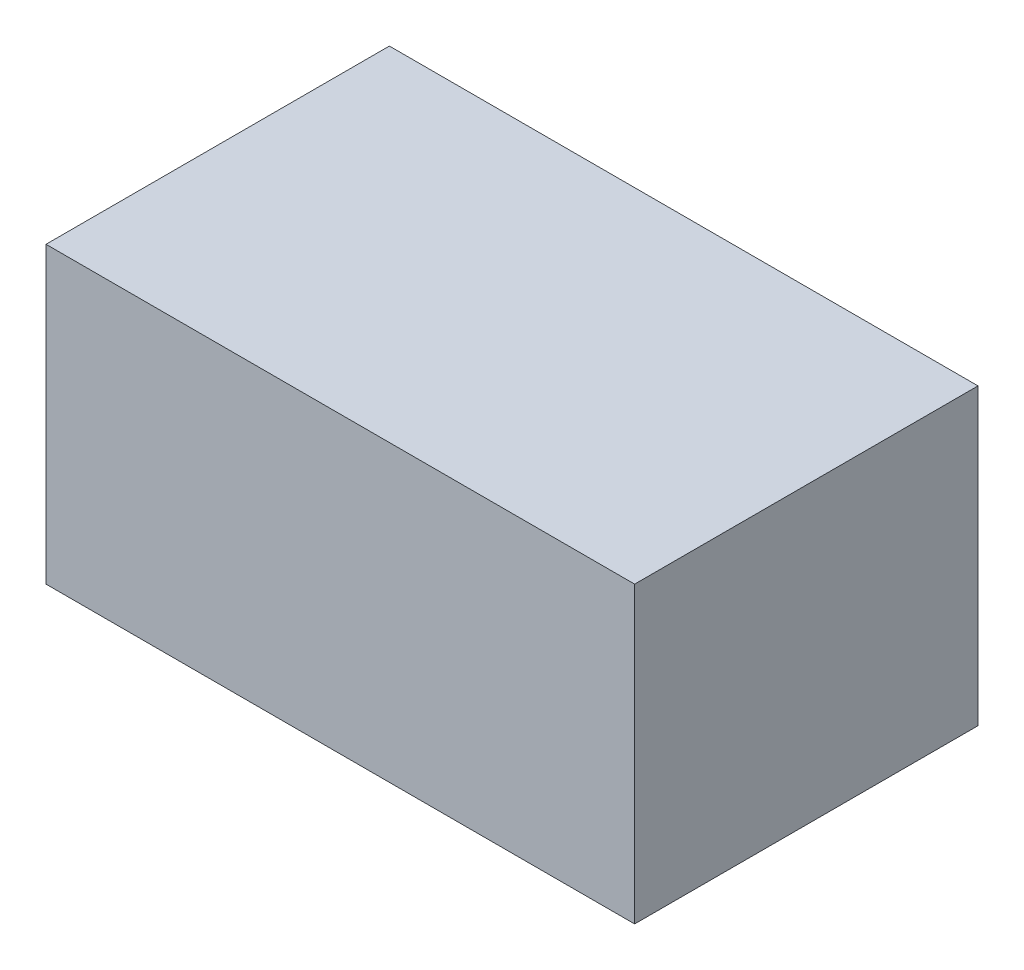
SolidWorks part; units mm, degrees
ref_plane "Alzado" through (0, 0, 0) normal (0, 0, 1) x (1, 0, 0)
ref_plane "Planta" through (0, 0, 0) normal (0, 1, 0) x (1, 0, 0)
ref_plane "Vista lateral" through (0, 0, 0) normal (1, 0, 0) x (0, 0, -1)
sketch "Croquis1" plane through (0, 0, 0) normal (0, 1, 0) x (1, 0, 0)
  line L0 (-43.5, 33.5) -> (-43.5, -36.5)
  line L1 (-43.5, -36.5) -> (76.5, -36.5)
  line L2 (76.5, -36.5) -> (76.5, 33.5)
  line L3 (76.5, 33.5) -> (-43.5, 33.5)
  dimension "D1" = 70
  dimension "D2" = 120
  dimension "D3" = 43.5
  dimension "D4" = 33.5
extrude "Saliente-Extruir1" add sketch "Croquis1" along normal blind 60
sketch "Croquis2" plane through (0, 0, 0) normal (0, 1, 0) x (1, 0, 0)
  line L0 (-36.5, 26.5) -> (-36.5, -29.5)
  line L1 (-36.5, -29.5) -> (69.5, -29.5)
  line L2 (69.5, -29.5) -> (69.5, 26.5)
  line L3 (69.5, 26.5) -> (-36.5, 26.5)
  line L4 (-43.5, 33.5) -> (-43.5, -36.5) construction
  line L5 (76.5, 33.5) -> (-43.5, 33.5) construction
  line L6 (-43.5, -36.5) -> (76.5, -36.5) construction
  line L7 (76.5, -36.5) -> (76.5, 33.5) construction
  dimension "D1" = 7
  dimension "D2" = 7
  dimension "D3" = 7
  dimension "D4" = 7
extrude "Cortar-Extruir1" cut sketch "Croquis2" along normal blind 53
sketch "Croquis3" plane through (-43.5, 0, 0) normal (-1, 0, 0) x (0, 0, 1)
  line L0 (-26.5, 53) -> (-26.5, 24)
  line L1 (-26.5, 24) -> (16.5, 24)
  line L2 (16.5, 24) -> (16.5, 53)
  line L3 (16.5, 53) -> (-26.5, 53)
  line L4 (-33.5, 60) -> (36.5, 60) construction
  line L5 (-33.5, 60) -> (-33.5, 0) construction
  dimension "D1" = 7
  dimension "D2" = 7
  dimension "D3" = 43
  dimension "D4" = 29
extrude "Cortar-Extruir2" cut sketch "Croquis3" against normal blind 20
sketch "Croquis4" plane through (0, 53, 0) normal (0, -1, 0) x (1, 0, 0)
  line L0 (-36.5, 21.1985) -> (-15.5, 21.1985)
  line L1 (-36.5, 16.5) -> (-36.5, 29.5) construction
  line L2 (-15.5, 21.1985) -> (-15.5, -26.5)
  line L3 (69.5, -26.5) -> (-43.5, -26.5) construction
  line L4 (-36.5, 21.1985) -> (-36.5, -26.5)
  line L5 (-36.5, -26.5) -> (-15.5, -26.5)
  dimension "D1" = 21
extrude "Saliente-Extruir2" add sketch "Croquis4" along normal blind 32
sketch "Croquis5" plane through (-36.5, 0, 0) normal (-1, 0, 0) x (0, 0, 1)
  line L0 (-26.5, 53) -> (-26.5, 24)
  line L1 (-26.5, 24) -> (16.5, 24)
  line L2 (16.5, 24) -> (16.5, 53)
  line L3 (16.5, 53) -> (-26.5, 53)
extrude "Cortar-Extruir3" cut sketch "Croquis5" against normal blind 16
